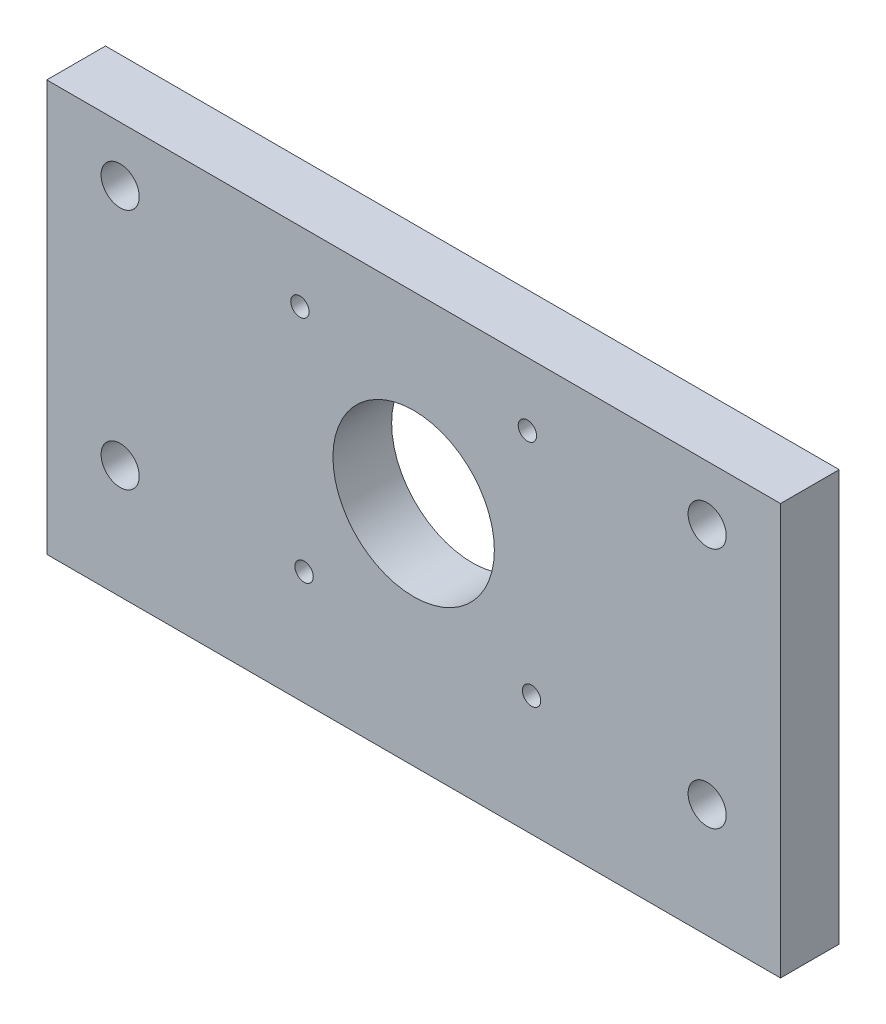
SolidWorks part; units mm, degrees
ref_plane "Ön Düzlem" through (0, 0, 0) normal (0, 0, 1) x (1, 0, 0)
ref_plane "Üst Düzlem" through (0, 0, 0) normal (0, 1, 0) x (1, 0, 0)
ref_plane "Sağ Düzlem" through (0, 0, 0) normal (1, 0, 0) x (0, 0, -1)
sketch "Çizim1" plane through (0, 0, 0) normal (0, 0, 1) x (1, 0, 0)
  line L1 (-42.6221, 26.9702) -> (57.3779, 26.9702)
  line L2 (-42.6221, 26.9702) -> (-42.6221, -29.0298)
  line L3 (-42.6221, -29.0298) -> (57.3779, -29.0298)
  line L4 (57.3779, 26.9702) -> (57.3779, -29.0298)
  circle A0 centre (7.3779, 1.9702) radius 2.8835
  dimension "D3" = 25
  dimension "D1" = 100
  dimension "D2" = 56
extrude "Yükseklik-Ekstrüzyon1" add sketch "Çizim1" along normal blind 8
sketch "Çizim2" plane through (0, 0, 0) normal (0, 0, -1) x (-1, 0, 0)
  circle A0 centre (-7.3779, 1.9702) radius 11
  circle A1 centre (8.1221, 17.4702) radius 1.25
  circle A2 centre (7.5534, -13.5298) radius 1.25
  circle A3 centre (-23.4466, -12.6701) radius 1.25
  circle A4 centre (-22.8779, 18.3299) radius 1.25
  dimension "D1" = 22
extrude "Kes-Ekstrüzyon1" cut sketch "Çizim2" against normal blind 10
sketch "Çizim3" plane through (0, 0, 8) normal (0, 0, 1) x (1, 0, 0)
  circle A0 centre (-32.6221, 19.4702) radius 2.6
  circle A1 centre (47.3779, 19.4702) radius 2.6
  circle A2 centre (47.3779, -13.5298) radius 2.6
  circle A3 centre (-32.6221, -13.5298) radius 2.6
extrude "Kes-Ekstrüzyon2" cut sketch "Çizim3" against normal blind 10
